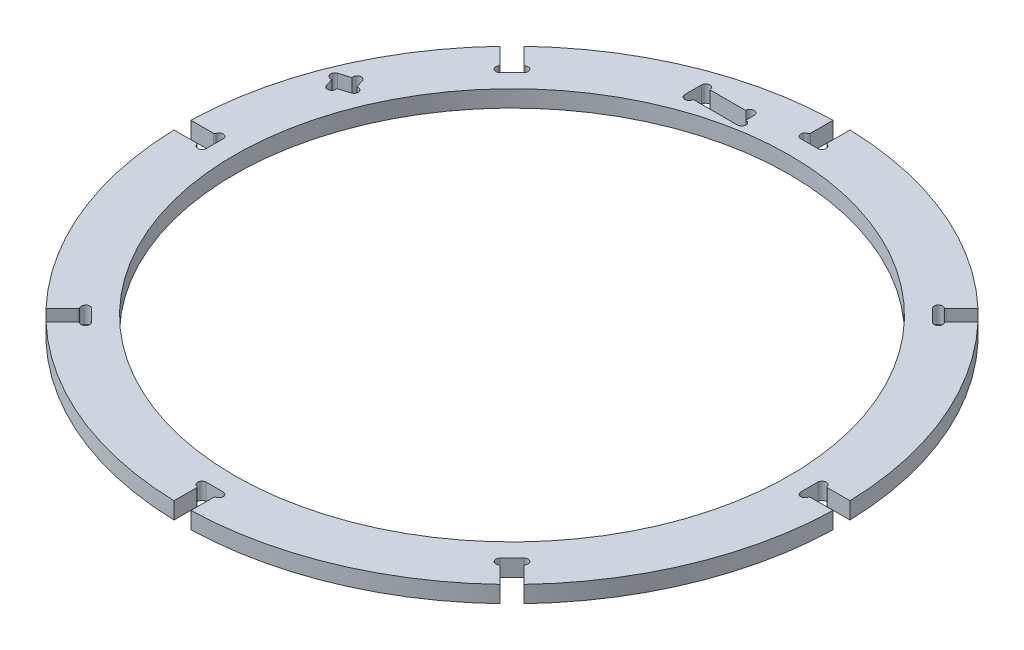
SolidWorks part; units mm, degrees
ref_plane "Front Plane" through (0, 0, 0) normal (0, 0, 1) x (1, 0, 0)
ref_plane "Top Plane" through (0, 0, 0) normal (0, 1, 0) x (1, 0, 0)
ref_plane "Right Plane" through (0, 0, 0) normal (1, 0, 0) x (0, 0, -1)
sketch "Sketch1" plane through (0, 0, 0) normal (0, 1, 0) x (1, 0, 0)
  circle A0 centre (0, 0) radius 210.5
  circle A1 centre (0, 0) radius 250
  dimension "D1" = 421
  dimension "D2" = 500
extrude "Boss-Extrude1" add sketch "Sketch1" along normal blind 12.7
sketch "Sketch2" plane through (0, 12.7, 0) normal (0, 1, 0) x (1, 0, 0)
  line L0 (0, 0) -> (0, 210.5) construction
  line L1 (0, 210.5) -> (0, 250) construction
  line L2 (0, 210.5) -> (0, 225.5) construction
  line L3 (0, 225.5) -> (0, 250) construction
  line L4 (6.4, 225.5) -> (6.4, 250) construction
  line L5 (-6.4, 225.5) -> (-6.4, 250) construction
  line L6 (6.4, 225.5) -> (-6.4, 225.5)
  line L7 (6.4, 250) -> (-6.4, 250)
  line L8 (-6.4, 250) -> (-6.4, 231.9)
  line L9 (6.4, 250) -> (6.4, 231.9)
  circle A0 centre (0, 0) radius 210.5 construction
  circle A1 centre (0, 0) radius 250 construction
  arc A2 (-6.4, 231.9) -> (-6.4, 225.5) centre (-6.4, 228.7) ccw
  arc A3 (6.4, 225.5) -> (6.4, 231.9) centre (6.4, 228.7) ccw
  dimension "D4" = 6.4
  dimension "D1" = 225.5
  dimension "D2" = 6.4
  dimension "D3" = 6.4
extrude "Cut-Extrude1" cut sketch "Sketch2" against normal through all
fillet "Fillet1" radius 1 2 edges at (6.4, 6.35, -231.9) (-6.4, 6.35, -231.9)
pattern_circular "CirPattern1" count 8 over 360 about axis through (0, 0, 0) along (0, 1, 0) of "Fillet1", "Cut-Extrude1"
sketch "Sketch5" plane through (0, 12.7, 0) normal (0, 1, 0) x (1, 0, 0)
  line L0 (0, 210.5) -> (-248.0445, 210.5)
  line L1 (-248.0445, 210.5) -> (-248.0445, 90.5)
  line L2 (-248.0445, 90.5) -> (-233.0445, 90.5)
  line L3 (0, 210.5) -> (0, 160.5)
  line L4 (0, 160.5) -> (-233.0445, 90.5)
  circle A0 centre (0, 0) radius 210.5 construction
  arc A1 (-181.2442, 172.1933) -> (-249.9181, 6.4) centre (0, 0) ccw construction
  dimension "D1" = 15
  dimension "D2" = 120
  dimension "D3" = 50
sketch "Sketch6" plane through (0, 12.7, 0) normal (0, 1, 0) x (1, 0, 0)
  line L0 (-6.4, 232.7792) -> (-6.4, 210.5) construction
  line L2 (-112.6133, 210.5) -> (-112.6133, 223.2) construction
  line L3 (-112.6133, 223.2) -> (-6.4, 223.2) construction
  line L4 (-112.6133, 210.5) -> (-6.4, 210.5) construction
  line L5 (-59.5067, 210.5) -> (-59.5067, 223.2) construction
  line L6 (-39.5067, 210.5) -> (-39.5067, 223.2)
  line L7 (-79.5067, 210.5) -> (-79.5067, 223.2)
  line L8 (-39.5067, 210.5) -> (-79.5067, 210.5)
  line L9 (-39.5067, 223.2) -> (-79.5067, 223.2) construction
  line L10 (-79.5067, 223.2) -> (-39.5067, 223.2)
  line L11 (-193.8983, 102.2584) -> (-241.9269, 87.832) construction
  line L13 (-193.8983, 102.2584) -> (-190.2448, 90.0953) construction
  line L14 (-190.2448, 90.0953) -> (-238.2734, 75.6688) construction
  line L15 (-238.2734, 75.6688) -> (-241.9269, 87.832) construction
  line L16 (-217.9126, 95.0452) -> (-214.2591, 82.8821) construction
  line L17 (-225.0956, 92.8876) -> (-221.4421, 80.7245)
  line L18 (-210.7296, 97.2028) -> (-207.0762, 85.0396) construction
  line L19 (-225.0956, 92.8876) -> (-210.7296, 97.2028)
  line L20 (-221.4421, 80.7245) -> (-207.0762, 85.0396) construction
  line L21 (-221.4421, 80.7245) -> (-207.0762, 85.0396)
  line L22 (-207.0762, 85.0396) -> (-210.7296, 97.2028)
  line L23 (0, 210.5) -> (-248.0445, 210.5) construction
  line L24 (0, 160.5) -> (-233.0445, 90.5) construction
  arc A0 (-6.4, 249.9181) -> (-172.1933, 181.2442) centre (0, 0) ccw construction
  circle A3 centre (0, 0) radius 210.5 construction
  arc A4 (-181.2442, 172.1933) -> (-249.9181, 6.4) centre (0, 0) ccw construction
  dimension "D1" = 12.7
  dimension "D5" = 12.7
  dimension "D2" = 20
  dimension "D3" = 20
  dimension "D6" = 7.5
  dimension "D7" = 7.5
extrude "Cut-Extrude4" cut sketch "Sketch6" against normal through all
sketch "Sketch7" plane through (0, 12.7, 0) normal (0, 1, 0) x (1, 0, 0)
  line L0 (-225.0956, 92.8876) -> (-221.4421, 80.7245) construction
  line L1 (-221.4421, 80.7245) -> (-207.0762, 85.0396) construction
  line L2 (-207.0762, 85.0396) -> (-210.7296, 97.2028) construction
  line L3 (-210.7296, 97.2028) -> (-225.0956, 92.8876) construction
  line L4 (-39.5067, 223.2) -> (-79.5067, 223.2) construction
  line L5 (-39.5067, 210.5) -> (-39.5067, 223.2) construction
  line L6 (-79.5067, 210.5) -> (-39.5067, 210.5) construction
  circle A0 centre (-224.175, 89.8229) radius 3.2
  circle A1 centre (-218.3774, 81.6451) radius 3.2
  circle A2 centre (-207.9967, 88.1043) radius 3.2
  circle A3 centre (-213.7944, 96.2822) radius 3.2
  circle A4 centre (-76.3067, 223.2) radius 3.2
  circle A5 centre (-42.7067, 223.2) radius 3.2
  circle A6 centre (-39.5067, 213.7) radius 3.2
  circle A7 centre (-76.3067, 210.5) radius 3.2
  dimension "D1" = 6.4
extrude "Cut-Extrude5" cut sketch "Sketch7" against normal through all
